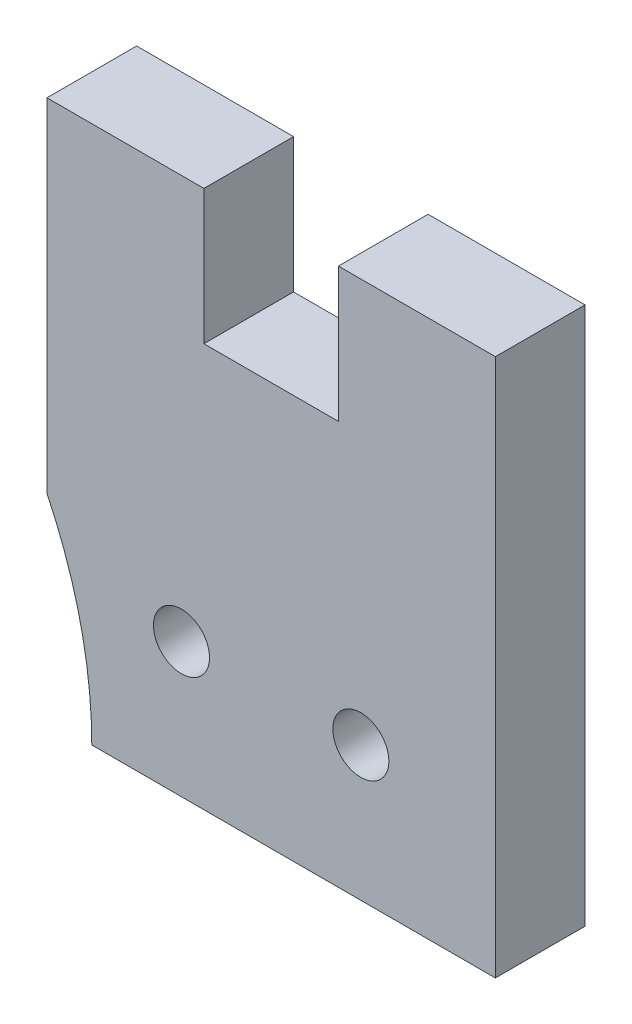
SolidWorks part; units mm, degrees
ref_plane "Plan de face" through (0, 0, 0) normal (0, 0, 1) x (1, 0, 0)
ref_plane "Plan de dessus" through (0, 0, 0) normal (0, 1, 0) x (1, 0, 0)
ref_plane "Plan de droite" through (0, 0, 0) normal (1, 0, 0) x (0, 0, -1)
sketch "Esquisse1" plane through (0, 0, 0) normal (0, 0, 1) x (1, 0, 0)
  line L0 (0, 0) -> (9, 0)
  line L1 (9, 0) -> (9, 12)
  line L2 (9, 12) -> (5.5, 12)
  line L3 (5.5, 12) -> (5.5, 9)
  line L4 (5.5, 9) -> (2.5, 9)
  line L5 (2.5, 9) -> (2.5, 12)
  line L6 (2.5, 12) -> (-1, 12)
  line L7 (-1, 12) -> (-1, 4.3589)
  line L8 (0, 0) -> (-10, 0) construction
  arc A0 (0, 0) -> (-1, 4.3589) centre (-10, 0) ccw
  dimension "D8" = 10
  dimension "D1" = 9
  dimension "D2" = 12
  dimension "D3" = 3.5
  dimension "D4" = 3
  dimension "D5" = 3
  dimension "D6" = 3
  dimension "D7" = 3.5
extrude "Boss.-Extru.2" add sketch "Esquisse1" along normal blind 1 and the other way blind 1 contours L6 L7 A0 L0 L1 L2 L3 L4 L5
sketch "Esquisse3" plane through (0, 0, 1) normal (0, 0, 1) x (1, 0, 0)
  line L0 (9, 0) -> (9, 3) construction
  line L1 (9, 0) -> (9, 12) construction
  line L2 (9, 3) -> (6, 3) construction
  line L3 (6, 3) -> (2, 3) construction
  circle A0 centre (2, 3) radius 0.625
  circle A1 centre (6, 3) radius 0.625
  dimension "D4" = 1.25
  dimension "D5" = 1.25
  dimension "D1" = 3
  dimension "D2" = 3
  dimension "D3" = 4
extrude "Enlèv. mat.-Extru.1" cut sketch "Esquisse3" against normal blind 10
